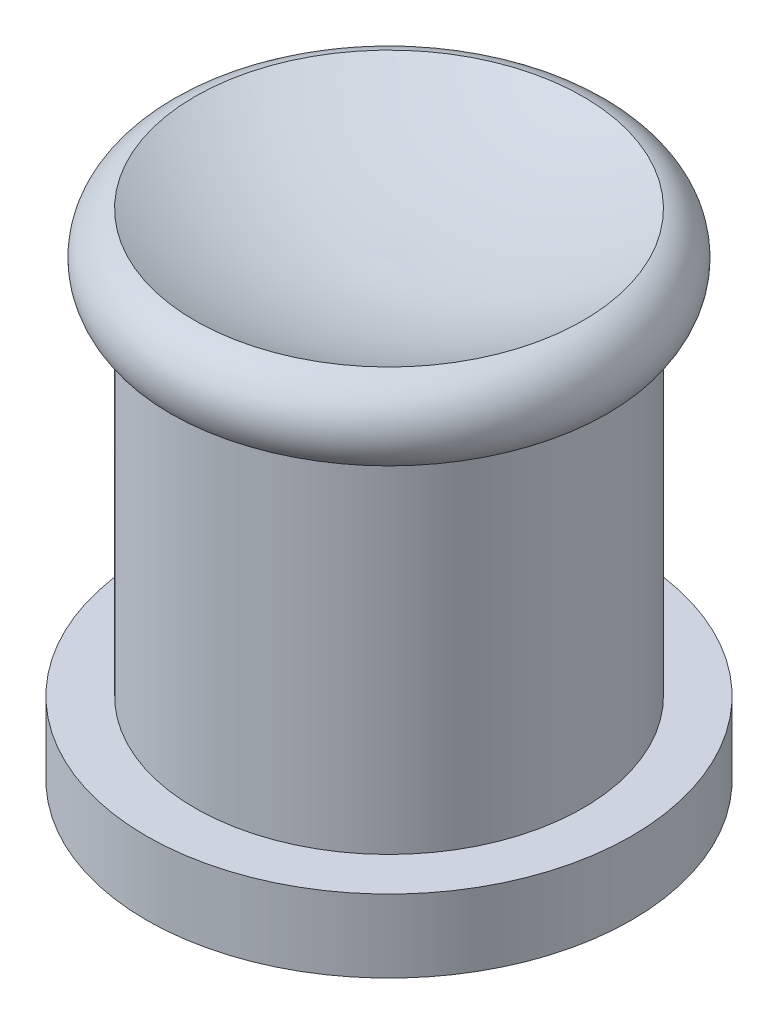
SolidWorks part; units mm, degrees
material "Brass"
ref_plane "Front Plane" through (0, 0, 0) normal (0, 0, 1) x (1, 0, 0)
ref_plane "Top Plane" through (0, 0, 0) normal (0, 1, 0) x (1, 0, 0)
ref_plane "Right Plane" through (0, 0, 0) normal (1, 0, 0) x (0, 0, -1)
sketch "Sketch1" plane through (0, 0, 0) normal (0, 0, 1) x (1, 0, 0)
  line L0 (0, 0.93) -> (0, -0.93) construction
  line L1 (0, 0) -> (0, 0.85)
  line L2 (0, 0.85) -> (0, 0.93)
  line L3 (0, 0) -> (0.5, 0)
  line L4 (0.5, 0) -> (0.5, 0.15)
  line L5 (0.5, 0.15) -> (0.4, 0.15)
  line L6 (0.4, 0.15) -> (0.4, 0.85)
  line L7 (0.4, 0.85) -> (0.45, 0.8789)
  arc A0 (0.45, 0.8789) -> (0.4, 1.02) centre (0.3779, 0.9328) ccw
  arc A1 (0, 0.93) -> (0.4, 1.02) centre (0.0303, 1.7294) ccw
  point P4 (0, 0)
  dimension "D1" = 0.85
  dimension "D6" = 0.4
  dimension "D7" = 0.09
  dimension "D10" = 0.8
  dimension "D2" = 0.08
  dimension "D3" = 0.5
  dimension "D4" = 0.15
  dimension "D5" = 120
  dimension "D8" = 0.17
  dimension "D9" = 0.45
  dimension "D11" = 0.7
revolve "Revolve1" add sketch "Sketch1" angle 360 about L0
